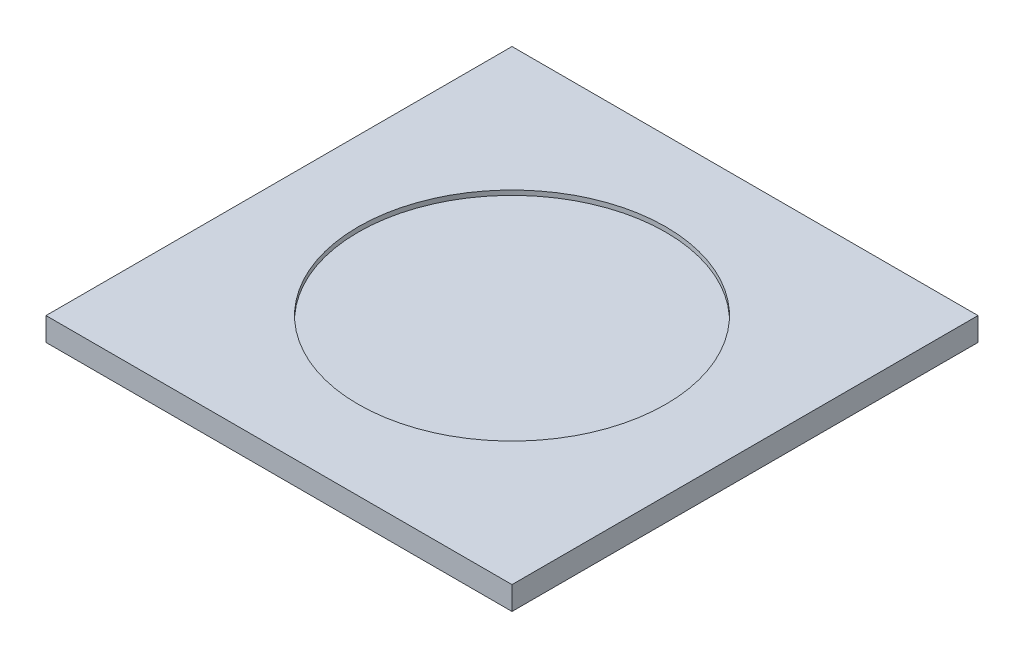
SolidWorks part; units mm, degrees
ref_plane "Front Plane" through (0, 0, 0) normal (0, 0, 1) x (1, 0, 0)
ref_plane "Top Plane" through (0, 0, 0) normal (0, 1, 0) x (1, 0, 0)
ref_plane "Right Plane" through (0, 0, 0) normal (1, 0, 0) x (0, 0, -1)
sketch "Sketch1" plane through (0, 0, 0) normal (0, 1, 0) x (1, 0, 0)
  line L1 (-1000, -1000) -> (1000, -1000)
  line L2 (-1000, -1000) -> (-1000, 1000)
  line L3 (-1000, 1000) -> (1000, 1000)
  line L4 (1000, -1000) -> (1000, 1000)
  line L5 (-1000, -1000) -> (1000, 1000) construction
  line L6 (-1000, 1000) -> (1000, -1000) construction
  point P0 (0, 0)
  dimension "D1" = 2000
  dimension "D2" = 2000
extrude "Boss-Extrude1" add sketch "Sketch1" along normal blind 100
sketch "Sketch2" plane through (0, 100, 0) normal (0, 1, 0) x (1, 0, 0)
  circle A0 centre (0, 0) radius 660
  dimension "D1" = 1320
extrude "Cut-Extrude1" cut sketch "Sketch2" against normal blind 20
